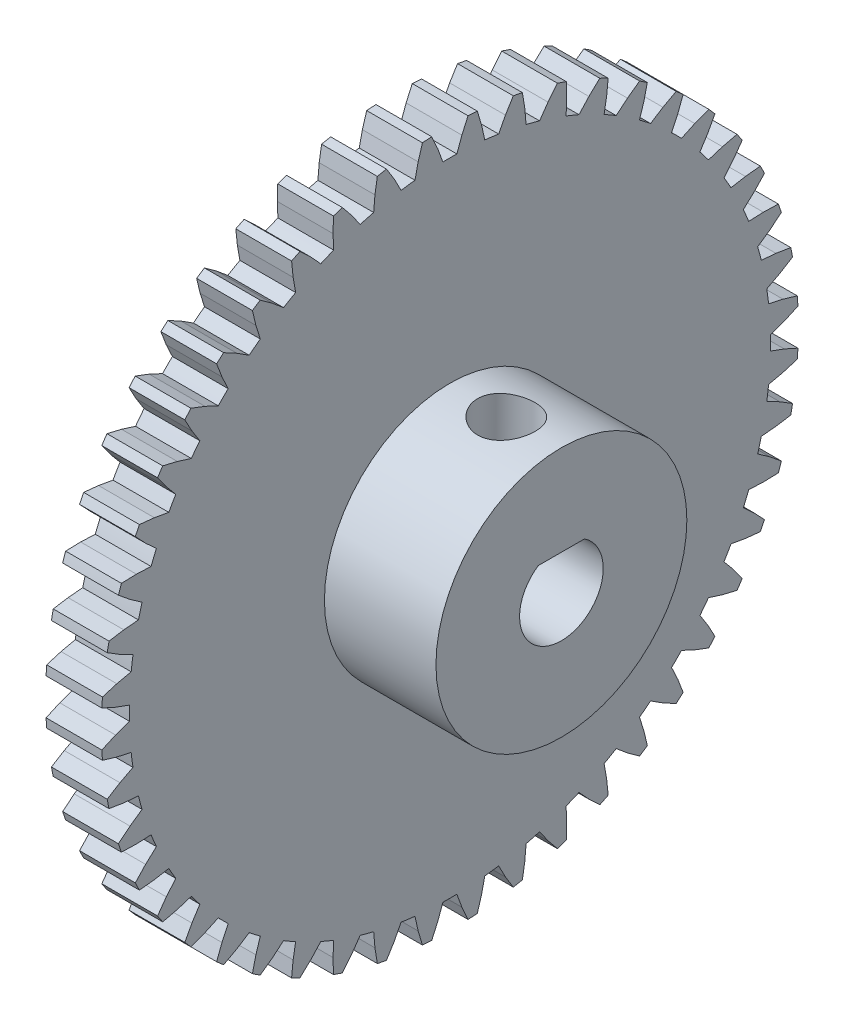
SolidWorks part; units mm, degrees
material "Plain Carbon Steel"
ref_plane "Front Plane" through (0, 0, 0) normal (0, 0, 1) x (1, 0, 0)
ref_plane "Top Plane" through (0, 0, 0) normal (0, 1, 0) x (1, 0, 0)
ref_plane "Right Plane" through (0, 0, 0) normal (1, 0, 0) x (0, 0, -1)
ref_plane "Plane1" through (2, 0, 0) normal (1, 0, 0) x (0, 0, -1)
sketch "Sketch1" plane through (2, 0, 0) normal (1, 0, 0) x (0, 0, -1)
  line L0 (-11.4973, -0.2509) -> (-11.9923, -0.431)
  line L1 (-11.9923, -0.431) -> (-12.483, -0.6512)
  line L2 (-12.4612, -0.9838) -> (-11.9459, -1.138)
  line L3 (-11.9459, -1.138) -> (-11.4316, -1.252)
  line L4 (-11.3662, -1.7494) -> (-11.8334, -1.9926)
  line L5 (-11.8334, -1.9926) -> (-12.2912, -2.2749)
  line L6 (-12.2262, -2.6019) -> (-11.6952, -2.6875)
  line L7 (-11.6952, -2.6875) -> (-11.1704, -2.7334)
  line L8 (-11.0406, -3.218) -> (-11.4721, -3.5202)
  line L9 (-11.4721, -3.5202) -> (-11.8891, -3.8598)
  line L10 (-11.782, -4.1755) -> (-11.2443, -4.191)
  line L11 (-11.2443, -4.191) -> (-10.7181, -4.168)
  line L12 (-10.5261, -4.6316) -> (-10.9145, -4.9875)
  line L13 (-10.9145, -4.9875) -> (-11.2836, -5.3786)
  line L14 (-11.1362, -5.6776) -> (-10.6011, -5.6228)
  line L15 (-10.6011, -5.6228) -> (-10.0824, -5.5314)
  line L16 (-9.8315, -5.9659) -> (-10.1701, -6.3694)
  line L17 (-10.1701, -6.3694) -> (-10.485, -6.8054)
  line L18 (-10.2999, -7.0826) -> (-9.7765, -6.9585)
  line L19 (-9.7765, -6.9585) -> (-9.2741, -6.8001)
  line L20 (-8.9687, -7.1981) -> (-9.2517, -7.6424)
  line L21 (-9.2517, -7.6424) -> (-9.5071, -8.1158)
  line L22 (-9.2873, -8.3664) -> (-8.7846, -8.175)
  line L23 (-8.7846, -8.175) -> (-8.3072, -7.9524)
  line L24 (-7.9524, -8.3072) -> (-8.175, -8.7846)
  line L25 (-8.175, -8.7846) -> (-8.3664, -9.2873)
  line L26 (-8.1158, -9.5071) -> (-7.6424, -9.2517)
  line L27 (-7.6424, -9.2517) -> (-7.1981, -8.9687)
  line L28 (-6.8001, -9.2741) -> (-6.9585, -9.7765)
  line L29 (-6.9585, -9.7765) -> (-7.0826, -10.2999)
  line L30 (-6.8054, -10.485) -> (-6.3694, -10.1701)
  line L31 (-6.3694, -10.1701) -> (-5.9659, -9.8315)
  line L32 (-5.5314, -10.0824) -> (-5.6228, -10.6011)
  line L33 (-5.6228, -10.6011) -> (-5.6776, -11.1362)
  line L34 (-5.3786, -11.2836) -> (-4.9875, -10.9145)
  line L35 (-4.9875, -10.9145) -> (-4.6316, -10.5261)
  line L36 (-4.168, -10.7181) -> (-4.191, -11.2443)
  line L37 (-4.191, -11.2443) -> (-4.1755, -11.782)
  line L38 (-3.8598, -11.8891) -> (-3.5202, -11.4721)
  line L39 (-3.5202, -11.4721) -> (-3.218, -11.0406)
  line L40 (-2.7334, -11.1704) -> (-2.6875, -11.6952)
  line L41 (-2.6875, -11.6952) -> (-2.6019, -12.2262)
  line L42 (-2.2749, -12.2912) -> (-1.9926, -11.8334)
  line L43 (-1.9926, -11.8334) -> (-1.7494, -11.3662)
  line L44 (-1.252, -11.4316) -> (-1.138, -11.9459)
  line L45 (-1.138, -11.9459) -> (-0.9838, -12.4612)
  line L46 (-0.6512, -12.483) -> (-0.431, -11.9923)
  line L47 (-0.431, -11.9923) -> (-0.2509, -11.4973)
  line L48 (0.2509, -11.4973) -> (0.431, -11.9923)
  line L49 (0.431, -11.9923) -> (0.6512, -12.483)
  line L50 (0.9838, -12.4612) -> (1.138, -11.9459)
  line L51 (1.138, -11.9459) -> (1.252, -11.4316)
  line L52 (1.7494, -11.3662) -> (1.9926, -11.8334)
  line L53 (1.9926, -11.8334) -> (2.2749, -12.2912)
  line L54 (2.6019, -12.2262) -> (2.6875, -11.6952)
  line L55 (2.6875, -11.6952) -> (2.7334, -11.1704)
  line L56 (3.218, -11.0406) -> (3.5202, -11.4721)
  line L57 (3.5202, -11.4721) -> (3.8598, -11.8891)
  line L58 (4.1755, -11.782) -> (4.191, -11.2443)
  line L59 (4.191, -11.2443) -> (4.168, -10.7181)
  line L60 (4.6316, -10.5261) -> (4.9875, -10.9145)
  line L61 (4.9875, -10.9145) -> (5.3786, -11.2836)
  line L62 (5.6776, -11.1362) -> (5.6228, -10.6011)
  line L63 (5.6228, -10.6011) -> (5.5314, -10.0824)
  line L64 (5.9659, -9.8315) -> (6.3694, -10.1701)
  line L65 (6.3694, -10.1701) -> (6.8054, -10.485)
  line L66 (7.0826, -10.2999) -> (6.9585, -9.7765)
  line L67 (6.9585, -9.7765) -> (6.8001, -9.2741)
  line L68 (7.1981, -8.9687) -> (7.6424, -9.2517)
  line L69 (7.6424, -9.2517) -> (8.1158, -9.5071)
  line L70 (8.3664, -9.2873) -> (8.175, -8.7846)
  line L71 (8.175, -8.7846) -> (7.9524, -8.3072)
  line L72 (8.3072, -7.9524) -> (8.7846, -8.175)
  line L73 (8.7846, -8.175) -> (9.2873, -8.3664)
  line L74 (9.5071, -8.1158) -> (9.2517, -7.6424)
  line L75 (9.2517, -7.6424) -> (8.9687, -7.1981)
  line L76 (9.2741, -6.8001) -> (9.7765, -6.9585)
  line L77 (9.7765, -6.9585) -> (10.2999, -7.0826)
  line L78 (10.485, -6.8054) -> (10.1701, -6.3694)
  line L79 (10.1701, -6.3694) -> (9.8315, -5.9659)
  line L80 (10.0824, -5.5314) -> (10.6011, -5.6228)
  line L81 (10.6011, -5.6228) -> (11.1362, -5.6776)
  line L82 (11.2836, -5.3786) -> (10.9145, -4.9875)
  line L83 (10.9145, -4.9875) -> (10.5261, -4.6316)
  line L84 (10.7181, -4.168) -> (11.2443, -4.191)
  line L85 (11.2443, -4.191) -> (11.782, -4.1755)
  line L86 (11.8891, -3.8598) -> (11.4721, -3.5202)
  line L87 (11.4721, -3.5202) -> (11.0406, -3.218)
  line L88 (11.1704, -2.7334) -> (11.6952, -2.6875)
  line L89 (11.6952, -2.6875) -> (12.2262, -2.6019)
  line L90 (12.2912, -2.2749) -> (11.8334, -1.9926)
  line L91 (11.8334, -1.9926) -> (11.3662, -1.7494)
  line L92 (11.4316, -1.252) -> (11.9459, -1.138)
  line L93 (11.9459, -1.138) -> (12.4612, -0.9838)
  line L94 (12.483, -0.6512) -> (11.9923, -0.431)
  line L95 (11.9923, -0.431) -> (11.4973, -0.2509)
  line L96 (11.4973, 0.2509) -> (11.9923, 0.431)
  line L97 (11.9923, 0.431) -> (12.483, 0.6512)
  line L98 (12.4612, 0.9838) -> (11.9459, 1.138)
  line L99 (11.9459, 1.138) -> (11.4316, 1.252)
  line L100 (11.3662, 1.7494) -> (11.8334, 1.9926)
  line L101 (11.8334, 1.9926) -> (12.2912, 2.2749)
  line L102 (12.2262, 2.6019) -> (11.6952, 2.6875)
  line L103 (11.6952, 2.6875) -> (11.1704, 2.7334)
  line L104 (11.0406, 3.218) -> (11.4721, 3.5202)
  line L105 (11.4721, 3.5202) -> (11.8891, 3.8598)
  line L106 (11.782, 4.1755) -> (11.2443, 4.191)
  line L107 (11.2443, 4.191) -> (10.7181, 4.168)
  line L108 (10.5261, 4.6316) -> (10.9145, 4.9875)
  line L109 (10.9145, 4.9875) -> (11.2836, 5.3786)
  line L110 (11.1362, 5.6776) -> (10.6011, 5.6228)
  line L111 (10.6011, 5.6228) -> (10.0824, 5.5314)
  line L112 (9.8315, 5.9659) -> (10.1701, 6.3694)
  line L113 (10.1701, 6.3694) -> (10.485, 6.8054)
  line L114 (10.2999, 7.0826) -> (9.7765, 6.9585)
  line L115 (9.7765, 6.9585) -> (9.2741, 6.8001)
  line L116 (8.9687, 7.1981) -> (9.2517, 7.6424)
  line L117 (9.2517, 7.6424) -> (9.5071, 8.1158)
  line L118 (9.2873, 8.3664) -> (8.7846, 8.175)
  line L119 (8.7846, 8.175) -> (8.3072, 7.9524)
  line L120 (7.9524, 8.3072) -> (8.175, 8.7846)
  line L121 (8.175, 8.7846) -> (8.3664, 9.2873)
  line L122 (8.1158, 9.5071) -> (7.6424, 9.2517)
  line L123 (7.6424, 9.2517) -> (7.1981, 8.9687)
  line L124 (6.8001, 9.2741) -> (6.9585, 9.7765)
  line L125 (6.9585, 9.7765) -> (7.0826, 10.2999)
  line L126 (6.8054, 10.485) -> (6.3694, 10.1701)
  line L127 (6.3694, 10.1701) -> (5.9659, 9.8315)
  line L128 (5.5314, 10.0824) -> (5.6228, 10.6011)
  line L129 (5.6228, 10.6011) -> (5.6776, 11.1362)
  line L130 (5.3786, 11.2836) -> (4.9875, 10.9145)
  line L131 (4.9875, 10.9145) -> (4.6316, 10.5261)
  line L132 (4.168, 10.7181) -> (4.191, 11.2443)
  line L133 (4.191, 11.2443) -> (4.1755, 11.782)
  line L134 (3.8598, 11.8891) -> (3.5202, 11.4721)
  line L135 (3.5202, 11.4721) -> (3.218, 11.0406)
  line L136 (2.7334, 11.1704) -> (2.6875, 11.6952)
  line L137 (2.6875, 11.6952) -> (2.6019, 12.2262)
  line L138 (2.2749, 12.2912) -> (1.9926, 11.8334)
  line L139 (1.9926, 11.8334) -> (1.7494, 11.3662)
  line L140 (1.252, 11.4316) -> (1.138, 11.9459)
  line L141 (1.138, 11.9459) -> (0.9838, 12.4612)
  line L142 (0.6512, 12.483) -> (0.431, 11.9923)
  line L143 (0.431, 11.9923) -> (0.2509, 11.4973)
  line L144 (-0.2509, 11.4973) -> (-0.431, 11.9923)
  line L145 (-0.431, 11.9923) -> (-0.6512, 12.483)
  line L146 (-0.9838, 12.4612) -> (-1.138, 11.9459)
  line L147 (-1.138, 11.9459) -> (-1.252, 11.4316)
  line L148 (-1.7494, 11.3662) -> (-1.9926, 11.8334)
  line L149 (-1.9926, 11.8334) -> (-2.2749, 12.2912)
  line L150 (-2.6019, 12.2262) -> (-2.6875, 11.6952)
  line L151 (-2.6875, 11.6952) -> (-2.7334, 11.1704)
  line L152 (-3.218, 11.0406) -> (-3.5202, 11.4721)
  line L153 (-3.5202, 11.4721) -> (-3.8598, 11.8891)
  line L154 (-4.1755, 11.782) -> (-4.191, 11.2443)
  line L155 (-4.191, 11.2443) -> (-4.168, 10.7181)
  line L156 (-4.6316, 10.5261) -> (-4.9875, 10.9145)
  line L157 (-4.9875, 10.9145) -> (-5.3786, 11.2836)
  line L158 (-5.6776, 11.1362) -> (-5.6228, 10.6011)
  line L159 (-5.6228, 10.6011) -> (-5.5314, 10.0824)
  line L160 (-5.9659, 9.8315) -> (-6.3694, 10.1701)
  line L161 (-6.3694, 10.1701) -> (-6.8054, 10.485)
  line L162 (-7.0826, 10.2999) -> (-6.9585, 9.7765)
  line L163 (-6.9585, 9.7765) -> (-6.8001, 9.2741)
  line L164 (-7.1981, 8.9687) -> (-7.6424, 9.2517)
  line L165 (-7.6424, 9.2517) -> (-8.1158, 9.5071)
  line L166 (-8.3664, 9.2873) -> (-8.175, 8.7846)
  line L167 (-8.175, 8.7846) -> (-7.9524, 8.3072)
  line L168 (-8.3072, 7.9524) -> (-8.7846, 8.175)
  line L169 (-8.7846, 8.175) -> (-9.2873, 8.3664)
  line L170 (-9.5071, 8.1158) -> (-9.2517, 7.6424)
  line L171 (-9.2517, 7.6424) -> (-8.9687, 7.1981)
  line L172 (-9.2741, 6.8001) -> (-9.7765, 6.9585)
  line L173 (-9.7765, 6.9585) -> (-10.2999, 7.0826)
  line L174 (-10.485, 6.8054) -> (-10.1701, 6.3694)
  line L175 (-10.1701, 6.3694) -> (-9.8315, 5.9659)
  line L176 (-10.0824, 5.5314) -> (-10.6011, 5.6228)
  line L177 (-10.6011, 5.6228) -> (-11.1362, 5.6776)
  line L178 (-11.2836, 5.3786) -> (-10.9145, 4.9875)
  line L179 (-10.9145, 4.9875) -> (-10.5261, 4.6316)
  line L180 (-10.7181, 4.168) -> (-11.2443, 4.191)
  line L181 (-11.2443, 4.191) -> (-11.782, 4.1755)
  line L182 (-11.8891, 3.8598) -> (-11.4721, 3.5202)
  line L183 (-11.4721, 3.5202) -> (-11.0406, 3.218)
  line L184 (-11.1704, 2.7334) -> (-11.6952, 2.6875)
  line L185 (-11.6952, 2.6875) -> (-12.2262, 2.6019)
  line L186 (-12.2912, 2.2749) -> (-11.8334, 1.9926)
  line L187 (-11.8334, 1.9926) -> (-11.3662, 1.7494)
  line L188 (-11.4316, 1.252) -> (-11.9459, 1.138)
  line L189 (-11.9459, 1.138) -> (-12.4612, 0.9838)
  line L190 (-12.483, 0.6512) -> (-11.9923, 0.431)
  line L191 (-11.9923, 0.431) -> (-11.4973, 0.2509)
  arc A0 (-12.483, -0.6512) -> (-12.4612, -0.9838) centre (0, 0) ccw
  arc A1 (-11.4316, -1.252) -> (-11.3662, -1.7494) centre (0, 0) ccw
  arc A2 (-12.2912, -2.2749) -> (-12.2262, -2.6019) centre (0, 0) ccw
  arc A3 (-11.1704, -2.7334) -> (-11.0406, -3.218) centre (0, 0) ccw
  arc A4 (-11.8891, -3.8598) -> (-11.782, -4.1755) centre (0, 0) ccw
  arc A5 (-10.7181, -4.168) -> (-10.5261, -4.6316) centre (0, 0) ccw
  arc A6 (-11.2836, -5.3786) -> (-11.1362, -5.6776) centre (0, 0) ccw
  arc A7 (-10.0824, -5.5314) -> (-9.8315, -5.9659) centre (0, 0) ccw
  arc A8 (-10.485, -6.8054) -> (-10.2999, -7.0826) centre (0, 0) ccw
  arc A9 (-9.2741, -6.8001) -> (-8.9687, -7.1981) centre (0, 0) ccw
  arc A10 (-9.5071, -8.1158) -> (-9.2873, -8.3664) centre (0, 0) ccw
  arc A11 (-8.3072, -7.9524) -> (-7.9524, -8.3072) centre (0, 0) ccw
  arc A12 (-8.3664, -9.2873) -> (-8.1158, -9.5071) centre (0, 0) ccw
  arc A13 (-7.1981, -8.9687) -> (-6.8001, -9.2741) centre (0, 0) ccw
  arc A14 (-7.0826, -10.2999) -> (-6.8054, -10.485) centre (0, 0) ccw
  arc A15 (-5.9659, -9.8315) -> (-5.5314, -10.0824) centre (0, 0) ccw
  arc A16 (-5.6776, -11.1362) -> (-5.3786, -11.2836) centre (0, 0) ccw
  arc A17 (-4.6316, -10.5261) -> (-4.168, -10.7181) centre (0, 0) ccw
  arc A18 (-4.1755, -11.782) -> (-3.8598, -11.8891) centre (0, 0) ccw
  arc A19 (-3.218, -11.0406) -> (-2.7334, -11.1704) centre (0, 0) ccw
  arc A20 (-2.6019, -12.2262) -> (-2.2749, -12.2912) centre (0, 0) ccw
  arc A21 (-1.7494, -11.3662) -> (-1.252, -11.4316) centre (0, 0) ccw
  arc A22 (-0.9838, -12.4612) -> (-0.6512, -12.483) centre (0, 0) ccw
  arc A23 (-0.2509, -11.4973) -> (0.2509, -11.4973) centre (0, 0) ccw
  arc A24 (0.6512, -12.483) -> (0.9838, -12.4612) centre (0, 0) ccw
  arc A25 (1.252, -11.4316) -> (1.7494, -11.3662) centre (0, 0) ccw
  arc A26 (2.2749, -12.2912) -> (2.6019, -12.2262) centre (0, 0) ccw
  arc A27 (2.7334, -11.1704) -> (3.218, -11.0406) centre (0, 0) ccw
  arc A28 (3.8598, -11.8891) -> (4.1755, -11.782) centre (0, 0) ccw
  arc A29 (4.168, -10.7181) -> (4.6316, -10.5261) centre (0, 0) ccw
  arc A30 (5.3786, -11.2836) -> (5.6776, -11.1362) centre (0, 0) ccw
  arc A31 (5.5314, -10.0824) -> (5.9659, -9.8315) centre (0, 0) ccw
  arc A32 (6.8054, -10.485) -> (7.0826, -10.2999) centre (0, 0) ccw
  arc A33 (6.8001, -9.2741) -> (7.1981, -8.9687) centre (0, 0) ccw
  arc A34 (8.1158, -9.5071) -> (8.3664, -9.2873) centre (0, 0) ccw
  arc A35 (7.9524, -8.3072) -> (8.3072, -7.9524) centre (0, 0) ccw
  arc A36 (9.2873, -8.3664) -> (9.5071, -8.1158) centre (0, 0) ccw
  arc A37 (8.9687, -7.1981) -> (9.2741, -6.8001) centre (0, 0) ccw
  arc A38 (10.2999, -7.0826) -> (10.485, -6.8054) centre (0, 0) ccw
  arc A39 (9.8315, -5.9659) -> (10.0824, -5.5314) centre (0, 0) ccw
  arc A40 (11.1362, -5.6776) -> (11.2836, -5.3786) centre (0, 0) ccw
  arc A41 (10.5261, -4.6316) -> (10.7181, -4.168) centre (0, 0) ccw
  arc A42 (11.782, -4.1755) -> (11.8891, -3.8598) centre (0, 0) ccw
  arc A43 (11.0406, -3.218) -> (11.1704, -2.7334) centre (0, 0) ccw
  arc A44 (12.2262, -2.6019) -> (12.2912, -2.2749) centre (0, 0) ccw
  arc A45 (11.3662, -1.7494) -> (11.4316, -1.252) centre (0, 0) ccw
  arc A46 (12.4612, -0.9838) -> (12.483, -0.6512) centre (0, 0) ccw
  arc A47 (11.4973, -0.2509) -> (11.4973, 0.2509) centre (0, 0) ccw
  arc A48 (12.483, 0.6512) -> (12.4612, 0.9838) centre (0, 0) ccw
  arc A49 (11.4316, 1.252) -> (11.3662, 1.7494) centre (0, 0) ccw
  arc A50 (12.2912, 2.2749) -> (12.2262, 2.6019) centre (0, 0) ccw
  arc A51 (11.1704, 2.7334) -> (11.0406, 3.218) centre (0, 0) ccw
  arc A52 (11.8891, 3.8598) -> (11.782, 4.1755) centre (0, 0) ccw
  arc A53 (10.7181, 4.168) -> (10.5261, 4.6316) centre (0, 0) ccw
  arc A54 (11.2836, 5.3786) -> (11.1362, 5.6776) centre (0, 0) ccw
  arc A55 (10.0824, 5.5314) -> (9.8315, 5.9659) centre (0, 0) ccw
  arc A56 (10.485, 6.8054) -> (10.2999, 7.0826) centre (0, 0) ccw
  arc A57 (9.2741, 6.8001) -> (8.9687, 7.1981) centre (0, 0) ccw
  arc A58 (9.5071, 8.1158) -> (9.2873, 8.3664) centre (0, 0) ccw
  arc A59 (8.3072, 7.9524) -> (7.9524, 8.3072) centre (0, 0) ccw
  arc A60 (8.3664, 9.2873) -> (8.1158, 9.5071) centre (0, 0) ccw
  arc A61 (7.1981, 8.9687) -> (6.8001, 9.2741) centre (0, 0) ccw
  arc A62 (7.0826, 10.2999) -> (6.8054, 10.485) centre (0, 0) ccw
  arc A63 (5.9659, 9.8315) -> (5.5314, 10.0824) centre (0, 0) ccw
  arc A64 (5.6776, 11.1362) -> (5.3786, 11.2836) centre (0, 0) ccw
  arc A65 (4.6316, 10.5261) -> (4.168, 10.7181) centre (0, 0) ccw
  arc A66 (4.1755, 11.782) -> (3.8598, 11.8891) centre (0, 0) ccw
  arc A67 (3.218, 11.0406) -> (2.7334, 11.1704) centre (0, 0) ccw
  arc A68 (2.6019, 12.2262) -> (2.2749, 12.2912) centre (0, 0) ccw
  arc A69 (1.7494, 11.3662) -> (1.252, 11.4316) centre (0, 0) ccw
  arc A70 (0.9838, 12.4612) -> (0.6512, 12.483) centre (0, 0) ccw
  arc A71 (0.2509, 11.4973) -> (-0.2509, 11.4973) centre (0, 0) ccw
  arc A72 (-0.6512, 12.483) -> (-0.9838, 12.4612) centre (0, 0) ccw
  arc A73 (-1.252, 11.4316) -> (-1.7494, 11.3662) centre (0, 0) ccw
  arc A74 (-2.2749, 12.2912) -> (-2.6019, 12.2262) centre (0, 0) ccw
  arc A75 (-2.7334, 11.1704) -> (-3.218, 11.0406) centre (0, 0) ccw
  arc A76 (-3.8598, 11.8891) -> (-4.1755, 11.782) centre (0, 0) ccw
  arc A77 (-4.168, 10.7181) -> (-4.6316, 10.5261) centre (0, 0) ccw
  arc A78 (-5.3786, 11.2836) -> (-5.6776, 11.1362) centre (0, 0) ccw
  arc A79 (-5.5314, 10.0824) -> (-5.9659, 9.8315) centre (0, 0) ccw
  arc A80 (-6.8054, 10.485) -> (-7.0826, 10.2999) centre (0, 0) ccw
  arc A81 (-6.8001, 9.2741) -> (-7.1981, 8.9687) centre (0, 0) ccw
  arc A82 (-8.1158, 9.5071) -> (-8.3664, 9.2873) centre (0, 0) ccw
  arc A83 (-7.9524, 8.3072) -> (-8.3072, 7.9524) centre (0, 0) ccw
  arc A84 (-9.2873, 8.3664) -> (-9.5071, 8.1158) centre (0, 0) ccw
  arc A85 (-8.9687, 7.1981) -> (-9.2741, 6.8001) centre (0, 0) ccw
  arc A86 (-10.2999, 7.0826) -> (-10.485, 6.8054) centre (0, 0) ccw
  arc A87 (-9.8315, 5.9659) -> (-10.0824, 5.5314) centre (0, 0) ccw
  arc A88 (-11.1362, 5.6776) -> (-11.2836, 5.3786) centre (0, 0) ccw
  arc A89 (-10.5261, 4.6316) -> (-10.7181, 4.168) centre (0, 0) ccw
  arc A90 (-11.782, 4.1755) -> (-11.8891, 3.8598) centre (0, 0) ccw
  arc A91 (-11.0406, 3.218) -> (-11.1704, 2.7334) centre (0, 0) ccw
  arc A92 (-12.2262, 2.6019) -> (-12.2912, 2.2749) centre (0, 0) ccw
  arc A93 (-11.3662, 1.7494) -> (-11.4316, 1.252) centre (0, 0) ccw
  arc A94 (-12.4612, 0.9838) -> (-12.483, 0.6512) centre (0, 0) ccw
  arc A95 (-11.4973, 0.2509) -> (-11.4973, -0.2509) centre (0, 0) ccw
extrude "Boss-Extrude1" add sketch "Sketch1" against normal blind 2
sketch "Sketch2" plane through (0, 0, 0) normal (0, 0, 1) x (1, 0, 0)
  line L0 (2, 4.5) -> (2, 0)
  line L1 (2, 0) -> (6, 0)
  line L2 (6, 0) -> (6, 4.5)
  line L3 (6, 4.5) -> (2, 4.5)
  line L4 (2, 0) -> (6, 0) construction
revolve "Revolve1" add sketch "Sketch2" angle 360 about L4
hole_wizard "Ø3.0 (3) Diameter Hole1" positions "Sketch4" profile "Sketch3" hole size "Ø3.0" standard "ANSI Metric"
sketch "Sketch4" plane through (6, 0, 0) normal (1, 0, 0) x (0, 0, -1)
  point P0 (0, 0)
sketch "Sketch3" plane through (6, 0, 0) normal (0, 1, 0) x (0, 0, -1)
  line L0 (0, 0) -> (0, 6)
  line L1 (0, 6) -> (1.5, 6)
  line L2 (1.5, 6) -> (1.5, 0)
  line L5 (1.5, 0) -> (0, 0)
  line L11 (0, -6.35) -> (0, 107.95) construction
  dimension "Thru Hole Dia." = 3
  dimension "Thru Hole Depth" = 6
ref_plane "Plane2" through (0, 1.0951, -0.0062) normal (0, -1, 0.0056) x (-1, 0, 0)
sketch "Sketch7" plane through (6, 0, 0) normal (1, 0, 0) x (0, 0, -1)
  line L0 (-0.8292, 1.25) -> (0.8292, 1.25)
  circle A0 centre (0, 0) radius 1.5 construction
  arc A1 (0.8292, 1.25) -> (-0.8292, 1.25) centre (0, 0) ccw
  circle M1 centre (0, 0) radius 1.5
  dimension "D1" = 1.25
extrude "Boss-Extrude2" add sketch "Sketch7" against normal up to surface (6 mm away) contours L0 M1
hole_wizard "M2.5x0.45 Tapped Hole1" positions "Sketch6" profile "Sketch5" tap size "M2.5x0.45" standard "ANSI Metric"
sketch "Sketch6" plane through (0, 1.0951, -0.0062) normal (0, -1, 0.0056) x (-1, 0, 0)
  point P0 (-4, 0)
sketch "Sketch5" plane through (4, 1.0951, -0.0062) normal (1, 0, 0) x (0, -0.0056, -1)
  line L0 (0, 0) -> (0, 3.4048)
  line L1 (0, 3.4048) -> (1.025, 3.4048)
  line L2 (1.025, 3.4048) -> (1.025, 0)
  line L5 (1.025, 0) -> (0, 0)
  line L11 (0, -6.35) -> (0, 107.95) construction
  dimension "Thread Major Dia." = 2.05
  dimension "Thru Tap Drill Depth" = 3.4048
